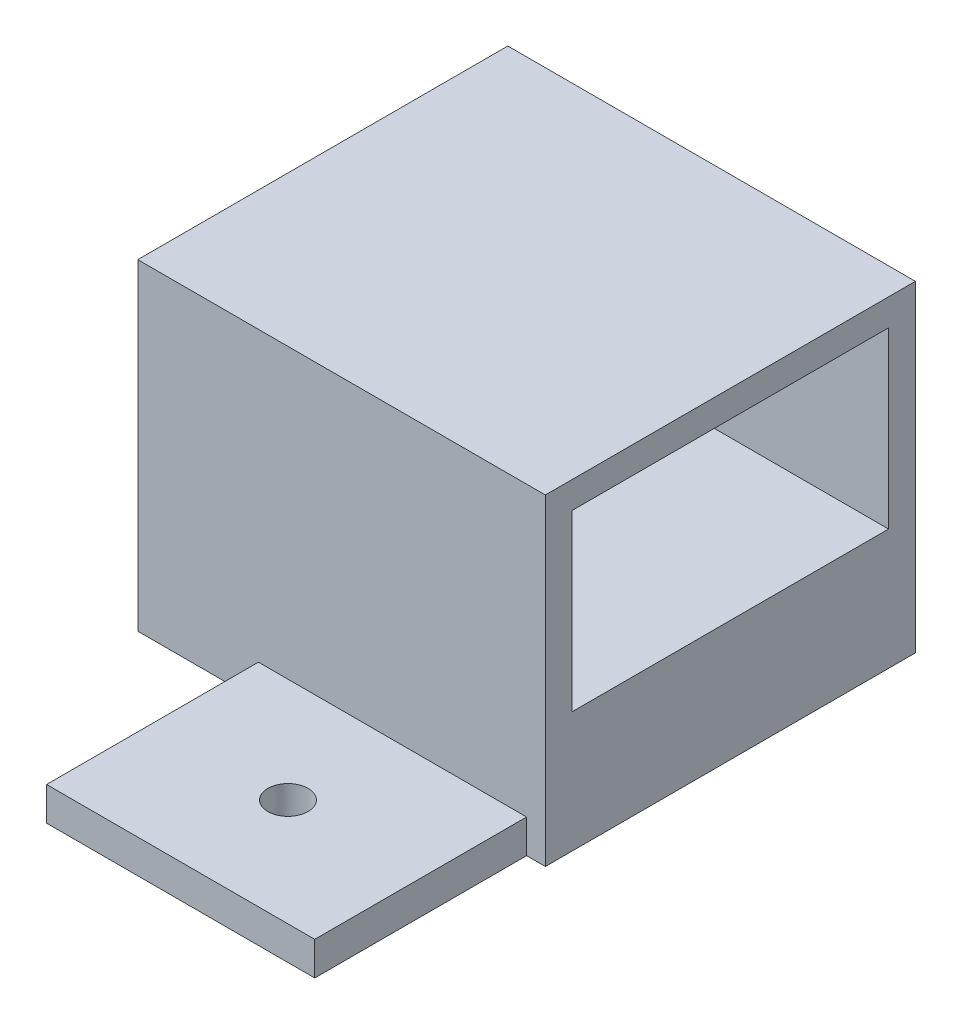
SolidWorks part; units mm, degrees
ref_plane "Front Plane" through (0, 0, 0) normal (0, 0, 1) x (1, 0, 0)
ref_plane "Top Plane" through (0, 0, 0) normal (0, 1, 0) x (1, 0, 0)
ref_plane "Right Plane" through (0, 0, 0) normal (1, 0, 0) x (0, 0, -1)
ref_plane "PZ_m34_000" through (0, 0, -34) normal (0, 0, 1) x (1, 0, 0)
sketch "S_box1" plane through (0, 0, -34) normal (0, 0, 1) x (1, 0, 0)
  line L0 (-10, 1.5) -> (10, 1.5)
  line L1 (10, 1.5) -> (10, 4)
  line L2 (10, 4) -> (-10, 4)
  line L3 (-10, 4) -> (-10, 1.5)
  dimension "P1" = 10
  dimension "P2" = 1.5
  dimension "P3" = 10
  dimension "P4" = 1.5
  dimension "P5" = 10
  dimension "P6" = 4
  dimension "P7" = 10
  dimension "P8" = 4
extrude "Boss_1" add sketch "S_box1" along normal blind 42
ref_plane "PZ_m35_400" through (0, 0, -35.4) normal (0, 0, 1) x (1, 0, 0)
sketch "S_box2" plane through (0, 0, -35.4) normal (0, 0, 1) x (1, 0, 0)
  line L0 (-19, 1.5) -> (11.4, 1.5)
  line L1 (11.4, 1.5) -> (11.4, 25.5)
  line L2 (11.4, 25.5) -> (-19, 25.5)
  line L3 (-19, 25.5) -> (-19, 1.5)
  dimension "P1" = 19
  dimension "P2" = 1.5
  dimension "P3" = 11.4
  dimension "P4" = 1.5
  dimension "P5" = 11.4
  dimension "P6" = 25.5
  dimension "P7" = 19
  dimension "P8" = 25.5
extrude "Boss_2" add sketch "S_box2" along normal blind 27.6
ref_plane "PZ_m33_400" through (0, 0, -33.4) normal (0, 0, 1) x (1, 0, 0)
sketch "S_cut3" plane through (0, 0, -33.4) normal (0, 0, 1) x (1, 0, 0)
  line L0 (-19.1, 10.5) -> (11.5, 10.5)
  line L1 (11.5, 10.5) -> (11.5, 23.5)
  line L2 (11.5, 23.5) -> (-19.1, 23.5)
  line L3 (-19.1, 23.5) -> (-19.1, 10.5)
  dimension "P1" = 19.1
  dimension "P2" = 10.5
  dimension "P3" = 11.5
  dimension "P4" = 10.5
  dimension "P5" = 11.5
  dimension "P6" = 23.5
  dimension "P7" = 19.1
  dimension "P8" = 23.5
extrude "Pocket_3" cut sketch "S_cut3" along normal blind 23.6
ref_plane "PZ_m35_500" through (0, 0, -35.5) normal (0, 0, 1) x (1, 0, 0)
sketch "S_cut4" plane through (0, 0, -35.5) normal (0, 0, 1) x (1, 0, 0)
  line L0 (-15, 4.5) -> (8, 4.5)
  line L1 (8, 4.5) -> (8, 8.5)
  line L2 (8, 8.5) -> (-15, 8.5)
  line L3 (-15, 8.5) -> (-15, 4.5)
  dimension "P1" = 15
  dimension "P2" = 4.5
  dimension "P3" = 8
  dimension "P4" = 4.5
  dimension "P5" = 8
  dimension "P6" = 8.5
  dimension "P7" = 15
  dimension "P8" = 8.5
extrude "Pocket_4" cut sketch "S_cut4" along normal blind 23.7
ref_plane "PY_p1_400" through (0, 1.4, 0) normal (0, 1, 0) x (1, 0, 0)
sketch "S_hole5" plane through (0, 1.4, 0) normal (0, 1, 0) x (1, 0, 0)
  circle A0 centre (0, 0) radius 1.5
  dimension "D1_S_hole5" = 3
extrude "Hole_5" cut sketch "S_hole5" along normal blind 2.7
equation "\"plate_t\" = 3"
equation "\"clearance\" = 0.4"
